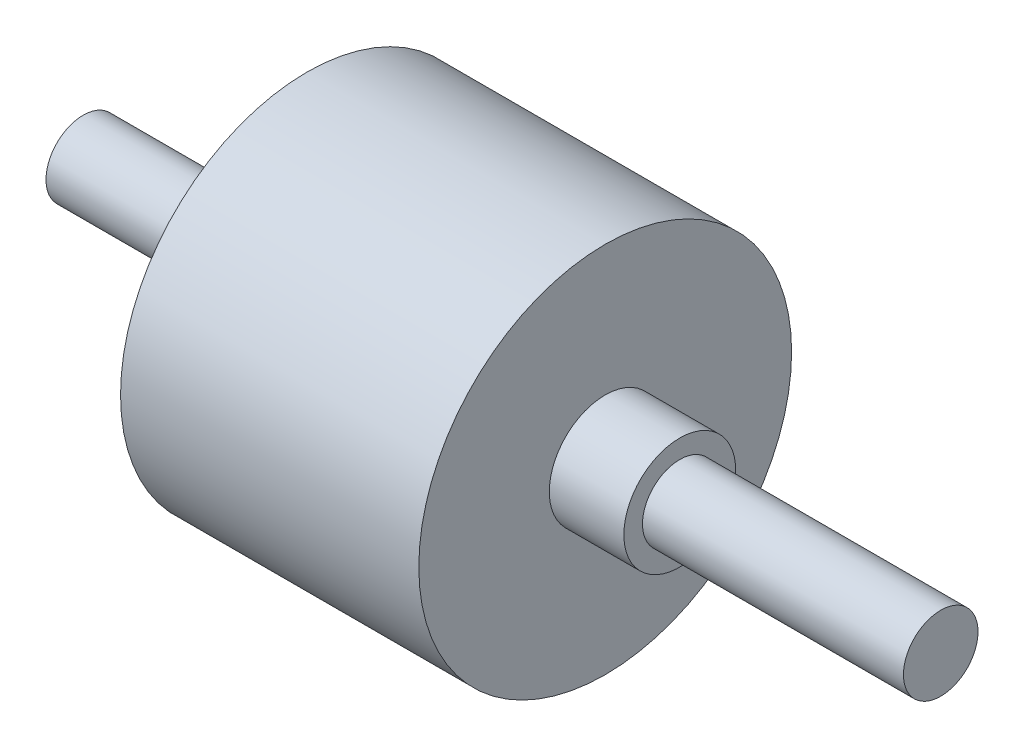
SolidWorks part; units mm, degrees
material "1023 Carbon Steel Sheet (SS)"
ref_plane "Front Plane" through (0, 0, 0) normal (0, 0, 1) x (1, 0, 0)
ref_plane "Top Plane" through (0, 0, 0) normal (0, 1, 0) x (1, 0, 0)
ref_plane "Right Plane" through (0, 0, 0) normal (1, 0, 0) x (0, 0, -1)
sketch "Sketch1" plane through (0, 0, 0) normal (0, 0, 1) x (1, 0, 0)
  line L0 (0, 0) -> (0, 5)
  line L1 (0, 5) -> (30, 5)
  line L2 (30, 5) -> (30, 25)
  line L3 (30, 25) -> (70, 25)
  line L4 (70, 25) -> (70, 7.5)
  line L5 (70, 7.5) -> (80, 7.5)
  line L6 (80, 7.5) -> (80, 5)
  line L7 (80, 5) -> (115, 5)
  line L8 (115, 5) -> (115, 0)
  line L9 (115, 0) -> (0, 0)
  dimension "D1" = 5
  dimension "D2" = 115
  dimension "D3" = 30
  dimension "D4" = 40
  dimension "D5" = 10
  dimension "D6" = 25
  dimension "D7" = 7.5
revolve "Revolve1" add sketch "Sketch1" angle 360 about L9
